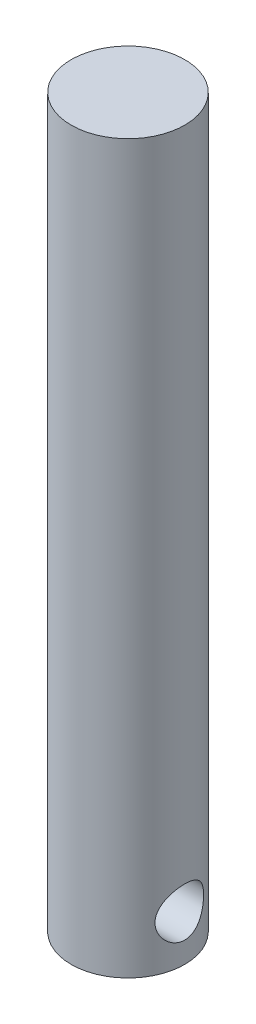
SolidWorks part; units mm, degrees
ref_plane "Front Plane" through (0, 0, 0) normal (0, 0, 1) x (1, 0, 0)
ref_plane "Top Plane" through (0, 0, 0) normal (0, 1, 0) x (1, 0, 0)
ref_plane "Right Plane" through (0, 0, 0) normal (1, 0, 0) x (0, 0, -1)
sketch "Sketch1" plane through (0, 0, 0) normal (0, 1, 0) x (1, 0, 0)
  circle A0 centre (0, 0) radius 3.9688
  dimension "D1" = 7.9375
extrude "Boss-Extrude1" add sketch "Sketch1" along normal blind 50.8
ref_plane "Plane1" through (3.9688, 0, 0) normal (1, 0, 0) x (0, 0, -1)
sketch "Sketch2" plane through (3.9688, 0, 0) normal (1, 0, 0) x (0, 0, -1)
  circle A0 centre (0, 3.175) radius 1.7
  point P2 (0, 0)
  dimension "D2" = 3.4
  dimension "D1" = 3.175
extrude "Cut-Extrude1" cut sketch "Sketch2" against normal up to next
